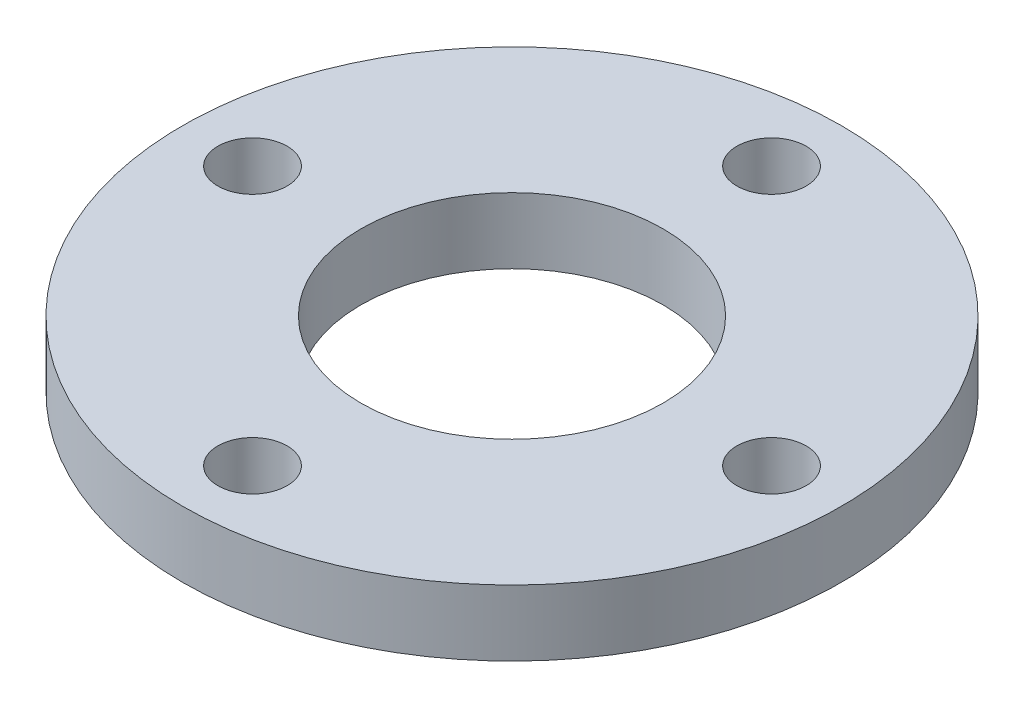
SolidWorks part; units mm, degrees
ref_plane "Front Plane" through (0, 0, 0) normal (0, 0, 1) x (1, 0, 0)
ref_plane "Top Plane" through (0, 0, 0) normal (0, 1, 0) x (1, 0, 0)
ref_plane "Right Plane" through (0, 0, 0) normal (1, 0, 0) x (0, 0, -1)
sketch "Sketch1" plane through (0, 0, 0) normal (0, 1, 0) x (1, 0, 0)
  line L0 (-15.0012, 0) -> (0, 0) construction
  line L1 (0, 0) -> (15.0012, 0) construction
  line L2 (0, 0) -> (0, 15.0012) construction
  line L3 (0, 0) -> (0, -15.0012) construction
  circle A0 centre (0, 0) radius 19.05
  circle A1 centre (0, 0) radius 8.7312
  circle A2 centre (15.0012, 0) radius 2
  circle A3 centre (0, 15.0012) radius 2
  circle A4 centre (-15.0012, 0) radius 2
  circle A5 centre (0, -15.0012) radius 2
  dimension "D1" = 38.1
  dimension "D2" = 17.4625
  dimension "D3" = 4
  dimension "D4" = 15.0012
extrude "Boss-Extrude1" add sketch "Sketch1" along normal blind 3.81
